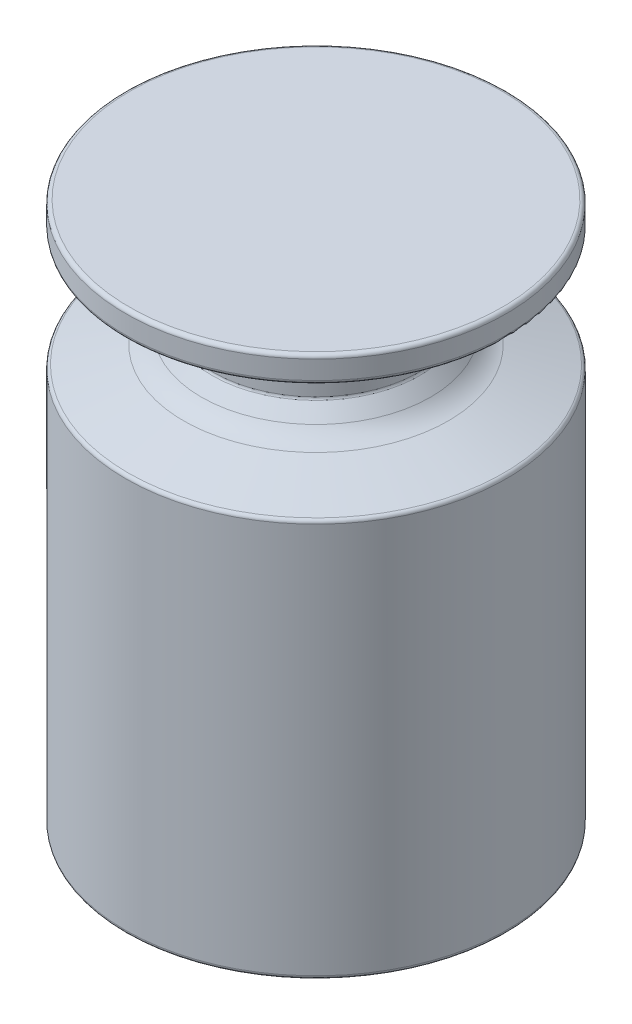
SolidWorks part; units mm, degrees
ref_plane "Front Plane" through (0, 0, 0) normal (0, 0, 1) x (1, 0, 0)
ref_plane "Top Plane" through (0, 0, 0) normal (0, 1, 0) x (1, 0, 0)
ref_plane "Right Plane" through (0, 0, 0) normal (1, 0, 0) x (0, 0, -1)
sketch "Sketch1" plane through (0, 0, 0) normal (0, 0, 1) x (1, 0, 0)
  line L0 (0, 67.0923) -> (0, -67.0923) construction
  line L1 (-25, 35.55) -> (25, 35.55) construction
  line L2 (-25, 35.55) -> (-25, -35.55) construction
  line L3 (-25, -35.55) -> (25, -35.55) construction
  line L4 (25, 35.55) -> (25, -35.55) construction
  line L5 (-25, 35.55) -> (25, -35.55) construction
  line L6 (-25, -35.55) -> (25, 35.55) construction
  line L7 (13.5, 24.45) -> (25, 24.45) construction
  line L8 (-25, 16.65) -> (25, 16.65) construction
  line L9 (-25, 16.65) -> (-25, -35.55) construction
  line L10 (-25, -35.55) -> (25, -35.55) construction
  line L11 (25, 16.65) -> (25, -35.55) construction
  line L12 (-25, 35.55) -> (25, 35.55) construction
  line L13 (-25, 35.55) -> (-25, 32.25) construction
  line L14 (-25, 32.25) -> (25, 32.25) construction
  line L15 (25, 35.55) -> (25, 32.25) construction
  line L16 (0, 32.25) -> (13.5, 32.25) construction
  line L17 (0, 32.25) -> (0, 16.65) construction
  line L18 (0, 16.65) -> (13.5, 16.65) construction
  line L19 (13.5, 32.25) -> (13.5, 16.65) construction
  line L20 (25, 32.25) -> (16, 29.4123)
  line L21 (13.5, 22.45) -> (13.5, 26.45)
  line L22 (13.5, 26.45) -> (16, 29.4123)
  line L23 (13.5, 22.45) -> (16, 19.4877)
  line L24 (25, 16.65) -> (16, 19.4877)
  line L25 (0, 35.55) -> (25, 35.55)
  line L26 (25, 35.55) -> (25, 32.25)
  line L27 (25, 16.65) -> (25, -35.55)
  line L28 (25, -35.55) -> (0, -35.55)
  line L29 (0, 35.55) -> (0, -35.55)
  point P0 (0, 0)
  point P9 (0, 0)
  point P22 (13.5, 24.45)
  dimension "D1" = 50
  dimension "D2" = 71.1
  dimension "D3" = 52.2
  dimension "D4" = 3.3
  dimension "D5" = 15.6
  dimension "D6" = 11.5
  dimension "D7" = 4
  dimension "D8" = 17.5
  dimension "D9" = 9
revolve "Revolve1" add sketch "Sketch1" angle 360 about L0
fillet "Fillet1" radius 5 2 edges at (0, 19.4877, 16) (0, 29.4123, 16)
fillet "Fillet2" radius 0.5 6 edges at (0, 26.45, 13.5) (0, 22.45, 13.5) (0, -35.55, 25) (0, 16.65, 25) (0, 32.25, 25) (0, 35.55, 25)
